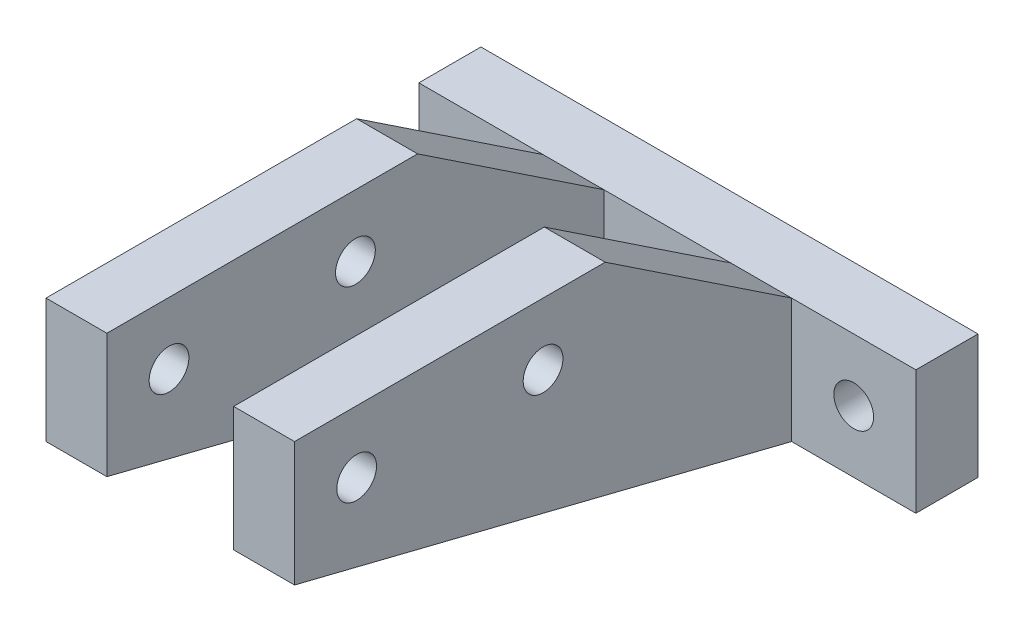
SolidWorks part; units mm, degrees
ref_plane "正面" through (0, 0, 0) normal (0, 0, 1) x (1, 0, 0)
ref_plane "平面" through (0, 0, 0) normal (0, 1, 0) x (1, 0, 0)
ref_plane "右側面" through (0, 0, 0) normal (1, 0, 0) x (0, 0, -1)
sketch "Sketch1" plane through (0, 0, 0) normal (0, 0, 1) x (1, 0, 0)
  line L1 (-20, 5) -> (20, 5)
  line L2 (-20, 5) -> (-20, -5)
  line L3 (-20, -5) -> (20, -5)
  line L4 (20, 5) -> (20, -5)
  line L5 (-20, 5) -> (20, -5) construction
  line L6 (-20, -5) -> (20, 5) construction
  point P0 (0, 0)
  dimension "D1" = 40
  dimension "D2" = 10
extrude "Boss-Extrude1" add sketch "Sketch1" along normal blind 5
sketch "Sketch2" plane through (0, 0, 5) normal (0, 0, 1) x (1, 0, 0)
  line L0 (0, 5) -> (0, -5) construction
  line L1 (20, 5) -> (-20, 5) construction
  line L2 (-20, -5) -> (20, -5) construction
  line L3 (10, 15) -> (5.1, 15)
  line L4 (-10, -5) -> (-5.1, -5)
  line L5 (-10, -5) -> (-10, 15)
  line L6 (-10, 15) -> (-5.1, 15)
  line L7 (-5.1, -5) -> (-5.1, 15)
  line L8 (5.1, -5) -> (5.1, 15)
  line L9 (10, -5) -> (5.1, -5)
  line L10 (10, -5) -> (10, 15)
  dimension "D1" = 5.1
  dimension "D2" = 4.9
  dimension "D3" = 20
extrude "Boss-Extrude2" add sketch "Sketch2" along normal blind 40
sketch "Sketch3" plane through (-10, 0, 0) normal (-1, 0, 0) x (0, 0, 1)
  line L0 (5, 10) -> (45, 10) construction
  line L1 (5, 15) -> (5, 5) construction
  line L2 (45, 15) -> (45, -5) construction
  line L3 (45, 15) -> (5, 15) construction
  circle A0 centre (40, 10) radius 1.6
  circle A1 centre (25, 10) radius 1.6
  dimension "D2" = 3.2
  dimension "D4" = 3.2
  dimension "D1" = 5
  dimension "D3" = 5
  dimension "D5" = 15
extrude "Cut-Extrude1" cut sketch "Sketch3" against normal up to surface (20 mm away) up to face at (10, 5, 21)
sketch "Sketch4" plane through (-10, 0, 0) normal (-1, 0, 0) x (0, 0, 1)
  line L0 (5, 5) -> (20, 15)
  line L1 (45, 15) -> (5, 15) construction
  line L2 (20, 15) -> (5, 15)
  line L3 (5, 15) -> (5, 5)
  dimension "D1" = 15
extrude "Cut-Extrude2" cut sketch "Sketch4" against normal up to surface (20 mm away) up to face at (10, 10, 41.6)
sketch "Sketch5" plane through (-10, 0, 0) normal (-1, 0, 0) x (0, 0, 1)
  line L0 (45, 5) -> (5, -5)
  line L1 (45, 15) -> (45, -5) construction
  line L2 (45, -5) -> (5, -5) construction
  line L3 (5, -5) -> (45, -5)
  line L4 (45, -5) -> (45, 5)
  dimension "D1" = 40
extrude "Cut-Extrude3" cut sketch "Sketch5" against normal up to surface (20 mm away) up to face at (10, 10, 41.6)
sketch "Sketch6" plane through (0, 0, 0) normal (0, 0, -1) x (-1, 0, 0)
  line L0 (-20, 0) -> (20, 0) construction
  line L1 (-20, -5) -> (-20, 5) construction
  line L2 (20, 5) -> (20, -5) construction
  line L3 (0, 5) -> (0, -5) construction
  line L4 (-20, 5) -> (20, 5) construction
  line L5 (20, -5) -> (-20, -5) construction
  circle A0 centre (-15, 0) radius 1.6
  circle A1 centre (15, 0) radius 1.6
  dimension "D1" = 3.2
  dimension "D2" = 5
extrude "Cut-Extrude4" cut sketch "Sketch6" against normal up to next
sketch "Sketch7" plane through (0, 0, 5) normal (0, 0, 1) x (1, 0, 0)
  line L0 (5.1, -5) -> (5.1, 5) construction
  line L1 (-5.1, -5) -> (5.1, -5)
  line L2 (-5.1, -5) -> (-5.1, -2)
  line L3 (-5.1, -2) -> (5.1, -2)
  line L4 (5.1, -5) -> (5.1, -2)
  dimension "D1" = 3
extrude "Boss-Extrude3" add sketch "Sketch7" along normal blind 40
sketch "Sketch8" plane through (-5.1, 0, 0) normal (-1, 0, 0) x (0, 0, 1)
  line L0 (5, -5) -> (25, 0)
  line L1 (45, 5) -> (5, -5) construction
  line L2 (25, 0) -> (45, 0)
  line L3 (45, 0) -> (45, -5)
  line L4 (45, -2) -> (45, -5) construction
  line L5 (45, -5) -> (5, -5)
extrude "Cut-Extrude5" cut sketch "Sketch8" against normal blind 40
sketch "Sketch10" plane through (0, 0, 5) normal (0, 0, 1) x (1, 0, 0)
  line L0 (5.1, -2) -> (5.1, 5) construction
  line L1 (-5.1, -2) -> (5.1, -2)
  line L2 (-5.1, -2) -> (-5.1, 0)
  line L3 (-5.1, 0) -> (5.1, 0)
  line L4 (5.1, -2) -> (5.1, 0)
  dimension "D1" = 2
extrude "Boss-Extrude4" add sketch "Sketch10" along normal blind 12
